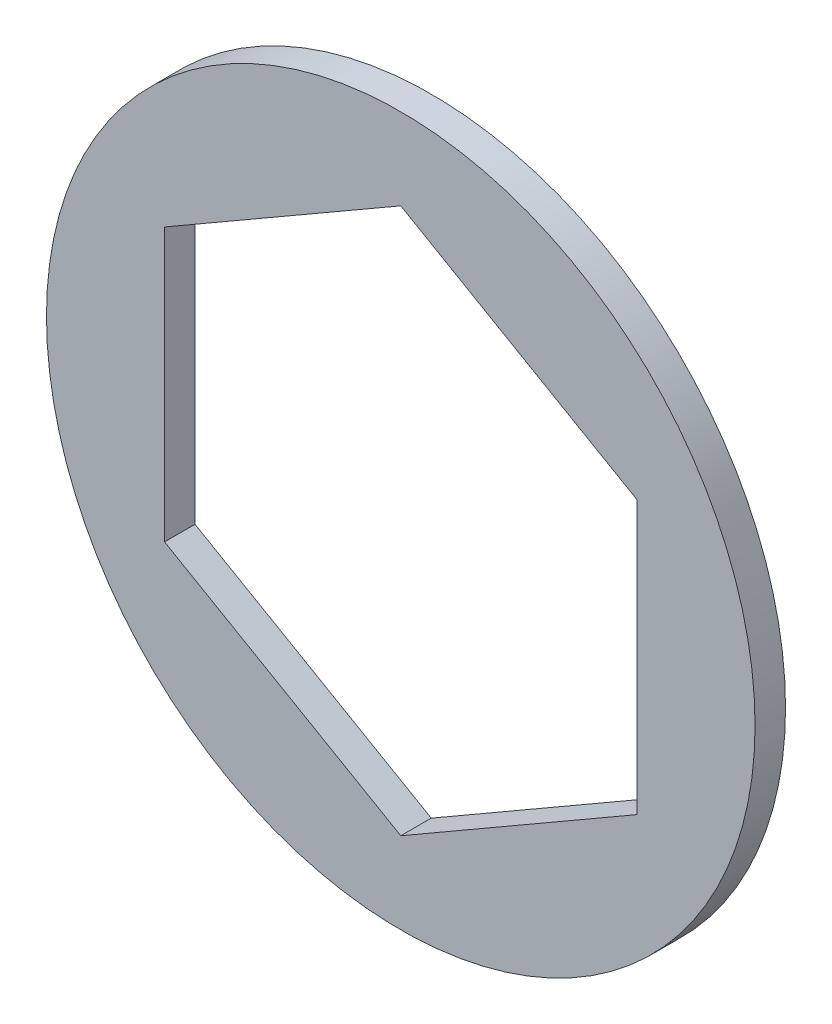
SolidWorks part; units mm, degrees
material "Nylon 101"
ref_plane "Front Plane" through (0, 0, 0) normal (0, 0, 1) x (1, 0, 0)
ref_plane "Top Plane" through (0, 0, 0) normal (0, 1, 0) x (1, 0, 0)
ref_plane "Right Plane" through (0, 0, 0) normal (1, 0, 0) x (0, 0, -1)
sketch "Sketch1" plane through (0, 0, 0) normal (0, 0, 1) x (1, 0, 0)
  line L1 (0, 7.3323) -> (-6.35, 3.6662)
  line L2 (-6.35, 3.6662) -> (-6.35, -3.6662)
  line L3 (-6.35, -3.6662) -> (0, -7.3323)
  line L4 (0, -7.3323) -> (6.35, -3.6662)
  line L5 (6.35, -3.6662) -> (6.35, 3.6662)
  line L6 (6.35, 3.6662) -> (0, 7.3323)
  circle A0 centre (0, 0) radius 9.525
  circle A1 centre (0, 0) radius 6.35 construction
  dimension "D1" = 12.7
  dimension "D2" = 19.05
extrude "Boss-Extrude1" add sketch "Sketch1" along normal mid plane 0.8192
